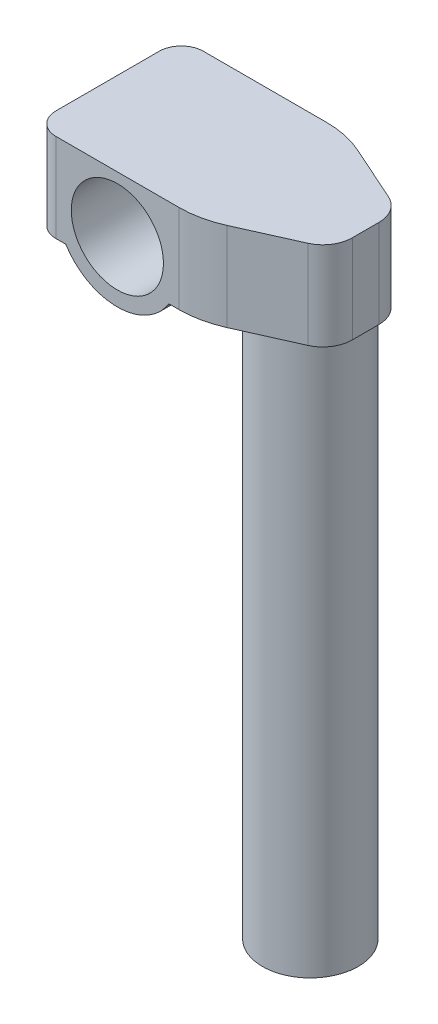
SolidWorks part; units mm, degrees
ref_plane "Front Plane" through (0, 0, 0) normal (0, 0, 1) x (1, 0, 0)
ref_plane "Top Plane" through (0, 0, 0) normal (0, 1, 0) x (1, 0, 0)
ref_plane "Right Plane" through (0, 0, 0) normal (1, 0, 0) x (0, 0, -1)
sketch "Sketch1" plane through (0, 0, 0) normal (0, 1, 0) x (1, 0, 0)
  line L0 (-35, 0) -> (35, 0) construction
  line L1 (4.4421, 20) -> (-29, 20)
  line L2 (-35, 14) -> (-35, -14)
  line L3 (-29, -20) -> (4.4421, -20)
  line L4 (15.0721, -17.7277) -> (30.2708, -10.9187)
  line L5 (35, -3.6179) -> (35, 3.6179)
  line L6 (30.2708, 10.9187) -> (15.0721, 17.7277)
  arc A0 (-35, -14) -> (-29, -20) centre (-29, -14) ccw
  arc A1 (-29, 20) -> (-35, 14) centre (-29, 14) ccw
  arc A2 (4.4421, -20) -> (15.0721, -17.7277) centre (4.4421, 6) ccw
  arc A3 (4.4421, 20) -> (15.0721, 17.7277) centre (4.4421, -6) cw
  arc A4 (30.2708, -10.9187) -> (35, -3.6179) centre (27, -3.6179) ccw
  arc A5 (35, 3.6179) -> (30.2708, 10.9187) centre (27, 3.6179) ccw
  point P11 (-35, -20)
  point P14 (-35, 20)
  point P17 (10, -20)
  point P20 (10, 20)
  point P23 (35, -8.8)
  point P26 (35, 8.8)
  dimension "D6" = 6
  dimension "D7" = 26
  dimension "D8" = 8
  dimension "D1" = 70
  dimension "D2" = 40
  dimension "D3" = 17.6
  dimension "D4" = 45
  dimension "D5" = 35
extrude "Boss-Extrude1" add sketch "Sketch1" along normal mid plane 20
sketch "Sketch2" plane through (0, 0, 20) normal (0, 0, 1) x (1, 0, 0)
  line L0 (-35, 10) -> (-23.9, 10)
  line L1 (-29, 10) -> (4.4421, 10) construction
  line L2 (35, 10) -> (-0.7753, 10)
  line L3 (-35, 6) -> (-26.3265, 6)
  line L4 (35, 6) -> (1.6512, 6)
  line L5 (-35, 10) -> (-35, 6)
  line L6 (35, 10) -> (35, 6)
  arc A0 (-23.9, 10) -> (-0.7753, 10) centre (-12.3377, 14.75) ccw
  arc A1 (-26.3265, 6) -> (1.6512, 6) centre (-12.3377, 14.75) ccw
  dimension "D2" = 12.5
  dimension "D1" = 4.75
  dimension "D3" = 11.1
  dimension "D4" = 4
extrude "Cut-Extrude1" cut sketch "Sketch2" against normal through all flip side to cut
sketch "Sketch3" plane through (0, 6, 0) normal (0, -1, 0) x (1, 0, 0)
  circle A0 centre (20, 0) radius 13
  dimension "D1" = 26
  dimension "D2" = 20
extrude "Boss-Extrude2" add sketch "Sketch3" along normal blind 150
ref_plane "Plane1" through (20, 0, 0) normal (1, 0, 0) x (0, 0, -1)
ref_plane "Plane2" through (0, 0, 50) normal (0, 0, 1) x (1, 0, 0)
sketch "Sketch8" plane through (0, 0, 0) normal (0, 0, 1) x (1, 0, 0)
  circle A0 centre (-12.3377, 14.75) radius 12.5
  arc A1 (-23.9, 10) -> (-0.7753, 10) centre (-12.3377, 14.75) ccw construction
  dimension "D1" = 25
ref_plane "Plane3" through (0, 10, 0) normal (0, 1, 0) x (1, 0, 0)
mirror "Mirror1" about plane through (0, 10, 0) normal (0, 1, 0) of "Boss-Extrude1"
sketch "Sketch15" plane through (0, 0, 20) normal (0, 0, 1) x (1, 0, 0)
  circle A0 centre (-12.3377, 14.75) radius 12.5
  dimension "D1" = 25
extrude "Cut-Extrude2" cut sketch "Sketch15" against normal through all
